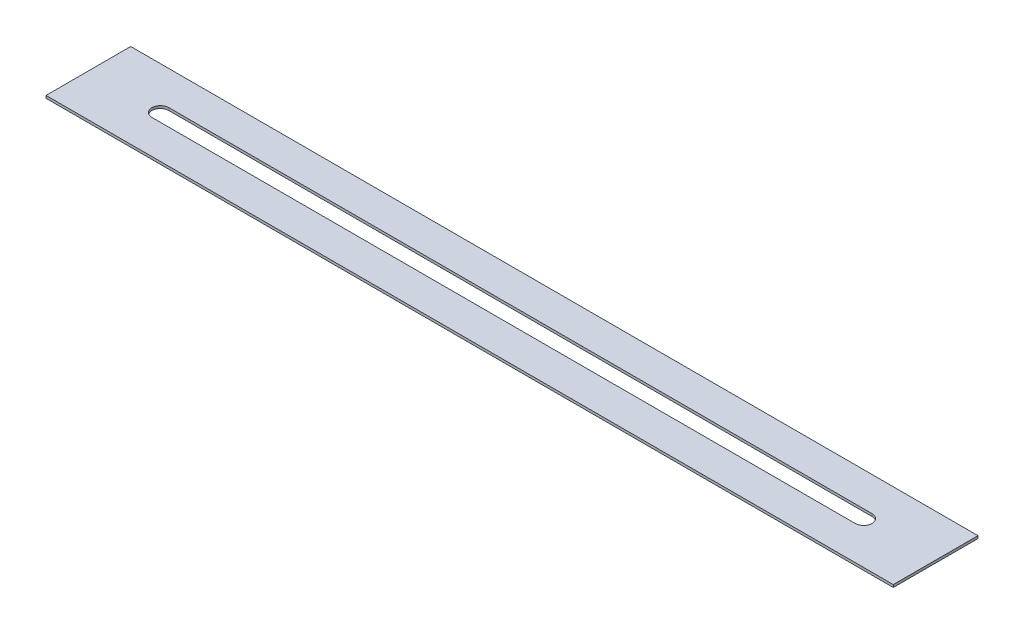
SolidWorks part; units mm, degrees
ref_plane "Front Plane" through (0, 0, 0) normal (0, 0, 1) x (1, 0, 0)
ref_plane "Top Plane" through (0, 0, 0) normal (0, 1, 0) x (1, 0, 0)
ref_plane "Right Plane" through (0, 0, 0) normal (1, 0, 0) x (0, 0, -1)
sketch "Sketch1" plane through (0, 0, 0) normal (0, 1, 0) x (1, 0, 0)
  line L0 (-415, 0) -> (415, 0) construction
  line L1 (-500, -50) -> (500, -50)
  line L2 (-500, -50) -> (-500, 50)
  line L3 (-500, 50) -> (500, 50)
  line L4 (500, -50) -> (500, 50)
  line L5 (-500, -50) -> (500, 50) construction
  line L6 (-500, 50) -> (500, -50) construction
  line L7 (-415, 10) -> (415, 10)
  line L8 (-415, -10) -> (415, -10)
  arc A0 (-415, 10) -> (-415, -10) centre (-415, 0) ccw
  arc A1 (415, -10) -> (415, 10) centre (415, 0) ccw
  point P0 (0, 0)
  point P8 (0, 0)
  dimension "D1" = 1000
  dimension "D2" = 100
  dimension "D3" = 40
  dimension "D4" = 85
extrude "Boss-Extrude2" add sketch "Sketch1" along normal blind 3
sketch "Sketch2" plane through (0, 3, 0) normal (0, 1, 0) x (1, 0, 0)
  line L0 (-500, -50) -> (500, -50) construction
  line L1 (-450, 50) -> (450, 50) construction
  line L2 (-450, 50) -> (-450, -50) construction
  line L3 (-450, -50) -> (450, -50) construction
  line L4 (450, 50) -> (450, -50) construction
  line L5 (-450, 50) -> (450, -50) construction
  line L6 (-450, -50) -> (450, 50) construction
  point P0 (0, 0)
  dimension "D1" = 900
